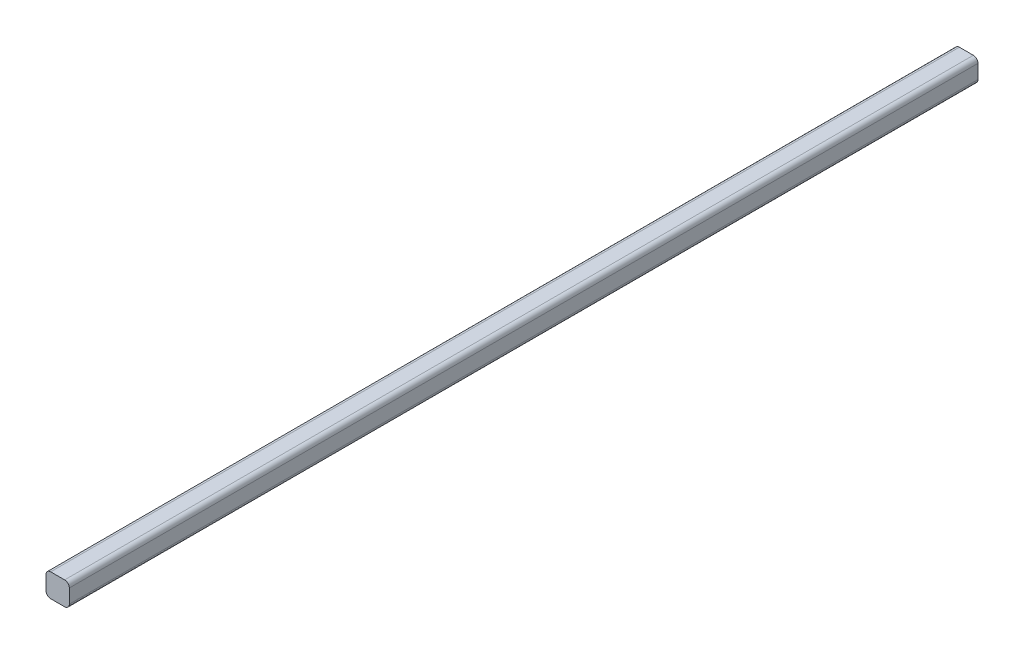
SolidWorks part; units mm, degrees
ref_plane "Plan de face" through (0, 0, 0) normal (0, 0, 1) x (1, 0, 0)
ref_plane "Plan de dessus" through (0, 0, 0) normal (0, 1, 0) x (1, 0, 0)
ref_plane "Plan de droite" through (0, 0, 0) normal (1, 0, 0) x (0, 0, -1)
sketch "Esquisse1" plane through (0, 0, 0) normal (0, 0, 1) x (1, 0, 0)
  line L1 (0, 0) -> (50, 0)
  line L2 (0, 0) -> (0, 50)
  line L3 (0, 50) -> (50, 50)
  line L4 (50, 0) -> (50, 50)
  dimension "D1" = 50
  dimension "D2" = 50
extrude "Boss.-Extru.1" add sketch "Esquisse1" along normal blind 1950
fillet "Congé1" radius 10 4 edges at (0, 0, 975) (50, 0, 975) (0, 50, 975) (50, 50, 975)
